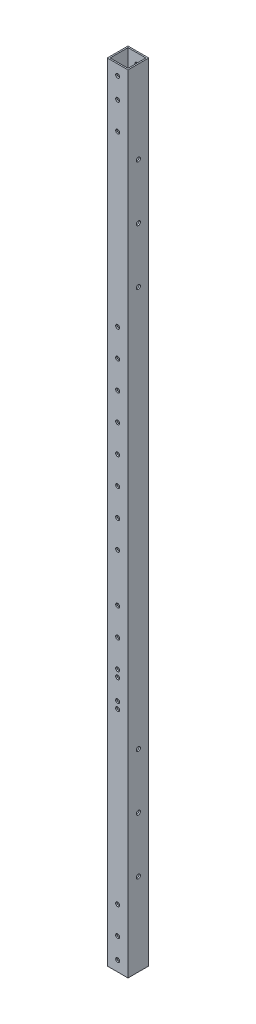
SolidWorks part; units mm, degrees
material "Thornel Mat VMA"
ref_plane "前视基准面" through (0, 0, 0) normal (0, 0, 1) x (1, 0, 0)
ref_plane "上视基准面" through (0, 0, 0) normal (0, 1, 0) x (1, 0, 0)
ref_plane "右视基准面" through (0, 0, 0) normal (1, 0, 0) x (0, 0, -1)
sketch "草图1" plane through (0, 0, 0) normal (0, 1, 0) x (1, 0, 0)
  line L1 (-7.5, -7.5) -> (7.5, -7.5)
  line L2 (-7.5, -7.5) -> (-7.5, 7.5)
  line L3 (-7.5, 7.5) -> (7.5, 7.5)
  line L4 (7.5, -7.5) -> (7.5, 7.5)
  line L5 (-7.5, -7.5) -> (7.5, 7.5) construction
  line L6 (-7.5, 7.5) -> (7.5, -7.5) construction
  point P0 (0, 0)
  dimension "D1" = 15
  dimension "D2" = 15
extrude "拉伸-薄壁1" add sketch "草图1" along normal blind 570 thin thin type one direction reverse wall 1
sketch "草图2" plane through (0, 0, 0) normal (0, 0, 1) x (1, 0, 0)
  line L0 (0, 0) -> (0, 570) construction
  line L1 (-7.5, 570) -> (7.5, 570) construction
  line L2 (-1000, 285) -> (49000, 285) construction
  line L3 (-7.5, 0) -> (7.5, 0) construction
  circle A0 centre (0, 7.5) radius 1.45
  circle A1 centre (0, 22.5) radius 1.45
  circle A2 centre (0, 42.5) radius 1.45
  circle A3 centre (0, 527.5) radius 1.45
  circle A4 centre (0, 547.5) radius 1.45
  circle A5 centre (0, 562.5) radius 1.45
  circle A6 centre (0, 285) radius 1.45
  circle A7 centre (0, 305) radius 1.45
  circle A8 centre (0, 265) radius 1.45
  circle A9 centre (0, 190) radius 1.45
  circle A10 centre (0, 170) radius 1.45
  circle A11 centre (0, 230) radius 1.45
  circle A12 centre (0, 210) radius 1.45
  circle A13 centre (0, 405) radius 1.45
  circle A14 centre (0, 385) radius 1.45
  circle A15 centre (0, 185) radius 1.45
  circle A16 centre (0, 165) radius 1.45
  circle A17 centre (0, 325) radius 1.45
  circle A18 centre (0, 345) radius 1.45
  circle A19 centre (0, 365) radius 1.45
  point P14 (0, 285)
  dimension "D1" = 2.9
  dimension "D5" = 2.9
  dimension "D9" = 20
  dimension "D10" = 20
  dimension "D11" = 20
  dimension "D12" = 100
  dimension "D13" = 20
  dimension "D14" = 40
  dimension "D15" = 20
  dimension "D16" = 20
  dimension "D2" = 7.5
  dimension "D3" = 15
  dimension "D4" = 20
  dimension "D6" = 20
  dimension "D7" = 20
  dimension "D8" = 170
extrude "切除-拉伸1" cut sketch "草图2" against normal through all and the other way blind 10
sketch "草图3" plane through (7.5, 0, 0) normal (1, 0, 0) x (0, 0, -1)
  line L0 (0, 0) -> (0, 570) construction
  line L1 (-7.5, 570) -> (7.5, 570) construction
  line L2 (-7.5, 0) -> (7.5, 0) construction
  line L3 (-1000, 285) -> (49000, 285) construction
  circle A0 centre (0, 60) radius 1.5
  circle A1 centre (0, 100) radius 1.5
  circle A2 centre (0, 470) radius 1.5
  circle A3 centre (0, 510) radius 1.5
  circle A4 centre (0, 140) radius 1.5
  circle A5 centre (0, 430) radius 1.5
  point P14 (0, 285)
  dimension "D1" = 3
  dimension "D4" = 40
  dimension "D2" = 60
  dimension "D3" = 40
extrude "切除-拉伸2" cut sketch "草图3" against normal through all
